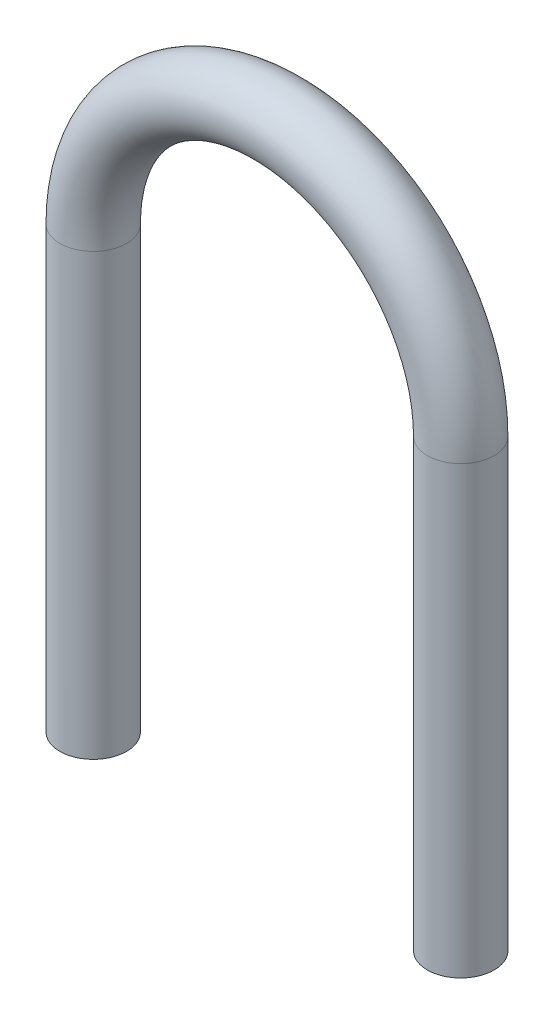
SolidWorks part; units mm, degrees
material "AISI 1020"
ref_plane "Front Plane" through (0, 0, 0) normal (0, 0, 1) x (1, 0, 0)
ref_plane "Top Plane" through (0, 0, 0) normal (0, 1, 0) x (1, 0, 0)
ref_plane "Right Plane" through (0, 0, 0) normal (1, 0, 0) x (0, 0, -1)
sketch "Sketch1" plane through (0, 0, 0) normal (0, 1, 0) x (1, 0, 0)
  line L0 (-16.5, 0) -> (0, 0) construction
  circle A0 centre (-16.5, 0) radius 3
  dimension "D1" = 6
  dimension "D2" = 16.5
sketch "Sketch2" plane through (0, 0, 0) normal (0, 0, 1) x (1, 0, 0)
  line L0 (-16.5, 0) -> (-16.5, 39.5)
  line L1 (-13.5, 0) -> (-19.5, 0) construction
  line L2 (16.5, -0.5) -> (16.5, 39.5)
  arc A2 (16.5, 39.5) -> (-16.5, 39.5) centre (0, 39.5) ccw
  dimension "D4" = 16.5
  dimension "D1" = 39.5
  dimension "D2" = 16.5
  dimension "D3" = 16.5
sweep "Sweep1" add profiles "Sketch1" path "Sketch2"
cosmetic thread "Cosmetic Thread1" parameters "D1"=26, "D2"=4.891
cosmetic thread "Cosmetic Thread2" parameters "D1"=26, "D2"=4.891
